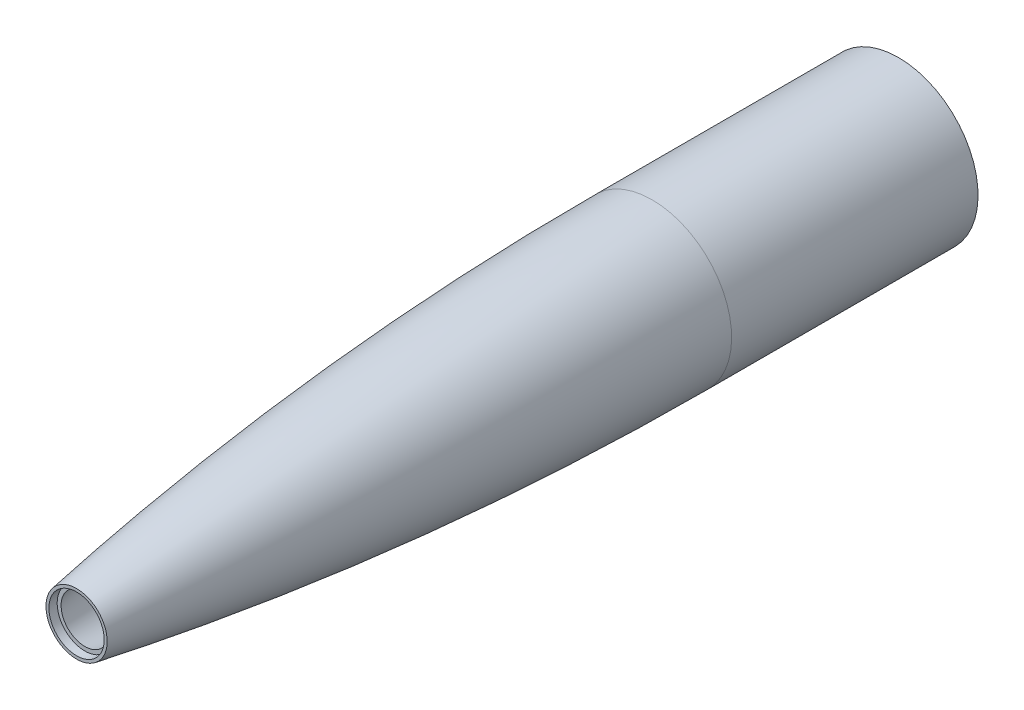
SolidWorks part; units mm, degrees
material "E-Glass Fiber"
ref_plane "Front Plane" through (0, 0, 0) normal (0, 0, 1) x (1, 0, 0)
ref_plane "Top Plane" through (0, 0, 0) normal (0, 1, 0) x (1, 0, 0)
ref_plane "Right Plane" through (0, 0, 0) normal (1, 0, 0) x (0, 0, -1)
sketch "Sketch1" plane through (0, 0, 0) normal (1, 0, 0) x (0, 0, -1)
  line L0 (0, 0) -> (-209.55, 0) construction
  line L1 (0, 20.28) -> (-62.82, 20.28)
  line L2 (0, 20.28) -> (0, 19.28)
  line L3 (0, 19.28) -> (-62.82, 19.28)
  line L7 (-209.55, 7.8) -> (-209.55, 7.05)
  line L8 (-209.55, 7.05) -> (-207.45, 7.05)
  line L9 (-207.45, 7.05) -> (-207.45, 6.05)
  arc A0 (-62.82, 20.28) -> (-209.55, 7.8) centre (-62.82, -848.5278) ccw
  arc A3 (-207.45, 6.05) -> (-62.82, 19.28) centre (-62.82, -777.8806) cw
  dimension "D4" = 209.55
  dimension "D1" = 62.82
  dimension "D2" = 1
  dimension "D3" = 20.28
  dimension "D5" = 7.8
  dimension "D6" = 0.75
  dimension "D7" = 2.1
  dimension "D8" = 1
revolve "Revolve1" add sketch "Sketch1" angle 360 about L0
